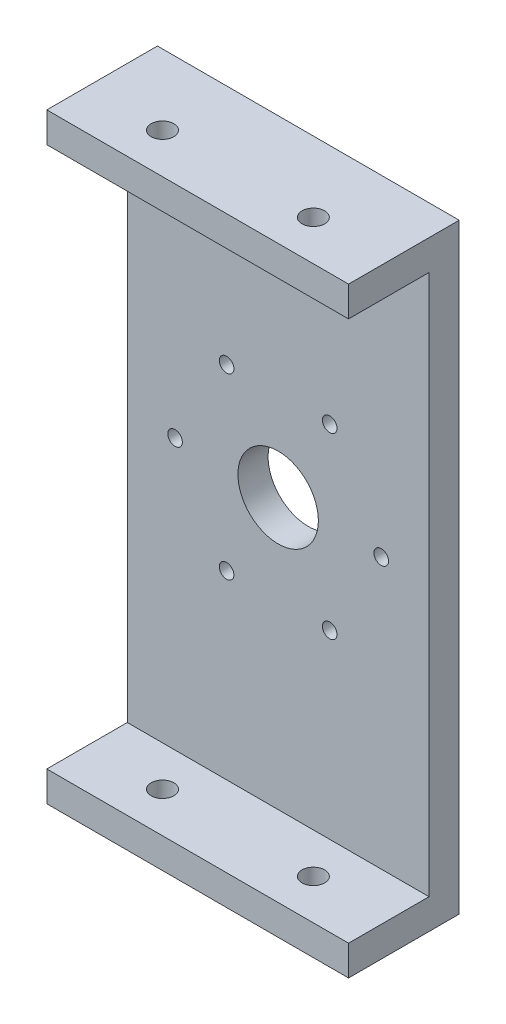
SolidWorks part; units mm, degrees
material "Aleación 6061"
ref_plane "Alzado" through (0, 0, 0) normal (0, 0, 1) x (1, 0, 0)
ref_plane "Planta" through (0, 0, 0) normal (0, 1, 0) x (1, 0, 0)
ref_plane "Vista lateral" through (0, 0, 0) normal (1, 0, 0) x (0, 0, -1)
sketch "Sk_Repisa" plane through (0, 0, 0) normal (0, 0, 1) x (1, 0, 0)
  line L1 (-30, -59.75) -> (30, -59.75)
  line L2 (-30, -59.75) -> (-30, 59.75)
  line L3 (-30, 59.75) -> (30, 59.75)
  line L4 (30, -59.75) -> (30, 59.75)
  line L5 (-30, -59.75) -> (30, 59.75) construction
  line L6 (-30, 59.75) -> (30, -59.75) construction
  point P0 (0, 0)
  dimension "D1" = 60
  dimension "D2" = 119.5
extrude "Repisa" add sketch "Sk_Repisa" along normal blind 6 from offset 373
sketch "Sk_Centro_motor" plane through (0, 0, 0) normal (0, 0, 1) x (1, 0, 0)
  circle A0 centre (0, 0) radius 8
  dimension "D1" = 16
extrude "Centro_motor" cut sketch "Sk_Centro_motor" along normal blind 6 from offset 373
sketch "Sk_Pasantes_M2-5_estator_J4" plane through (0, 0, 0) normal (0, 0, 1) x (1, 0, 0)
  circle A0 centre (20.5, 0) radius 1.45
  circle A1 centre (10.25, 17.7535) radius 1.45
  circle A2 centre (-10.25, 17.7535) radius 1.45
  circle A3 centre (-20.5, 0) radius 1.45
  circle A4 centre (-10.25, -17.7535) radius 1.45
  circle A5 centre (10.25, -17.7535) radius 1.45
  dimension "D1" = 2.9
  dimension "D3" = 2.9
  dimension "D6" = 2.9
  dimension "D9" = 2.9
  dimension "D11" = 2.9
  dimension "D14" = 2.9
  dimension "D2" = 20.5
  dimension "D4" = 10.25
  dimension "D5" = 17.7535
  dimension "D7" = 10.25
  dimension "D8" = 17.7535
  dimension "D10" = 20.5
  dimension "D12" = 10.25
  dimension "D13" = 17.7535
  dimension "D15" = 10.25
  dimension "D16" = 17.7535
extrude "Pasantes_M2-5_estator_J4" cut sketch "Sk_Pasantes_M2-5_estator_J4" along normal blind 6 from offset 373
sketch "Sk_Pestanas" plane through (0, 0, 0) normal (0, 0, 1) x (1, 0, 0)
  line L1 (-30, 53.75) -> (30, 53.75)
  line L2 (-30, 53.75) -> (-30, 59.75)
  line L3 (-30, 59.75) -> (30, 59.75)
  line L4 (30, 53.75) -> (30, 59.75)
  line L5 (-30, 53.75) -> (30, 59.75) construction
  line L6 (-30, 59.75) -> (30, 53.75) construction
  line L7 (-30, -59.75) -> (30, -59.75)
  line L8 (-30, -59.75) -> (-30, -53.75)
  line L9 (-30, -53.75) -> (30, -53.75)
  line L10 (30, -59.75) -> (30, -53.75)
  line L11 (-30, -59.75) -> (30, -53.75) construction
  line L12 (-30, -53.75) -> (30, -59.75) construction
  point P0 (0, 56.75)
  point P6 (0, -56.75)
  dimension "D1" = 60
  dimension "D2" = 6
  dimension "D3" = 56.75
  dimension "D4" = 60
  dimension "D5" = 6
  dimension "D6" = 56.75
extrude "Pestanas" add sketch "Sk_Pestanas" along normal blind 16 from offset 379
sketch "Sk_Pasantes_M4_pestanas" plane through (0, 0, 0) normal (0, 1, 0) x (1, 0, 0)
  circle A0 centre (-15, -387) radius 2.25
  circle A1 centre (15, -387) radius 2.25
  dimension "D1" = 4.5
  dimension "D4" = 4.5
  dimension "D2" = 15
  dimension "D3" = 387
  dimension "D5" = 15
  dimension "D6" = 387
extrude "Pasantes_M4_pestanas" cut sketch "Sk_Pasantes_M4_pestanas" along normal blind 119.5 from offset 59.75
